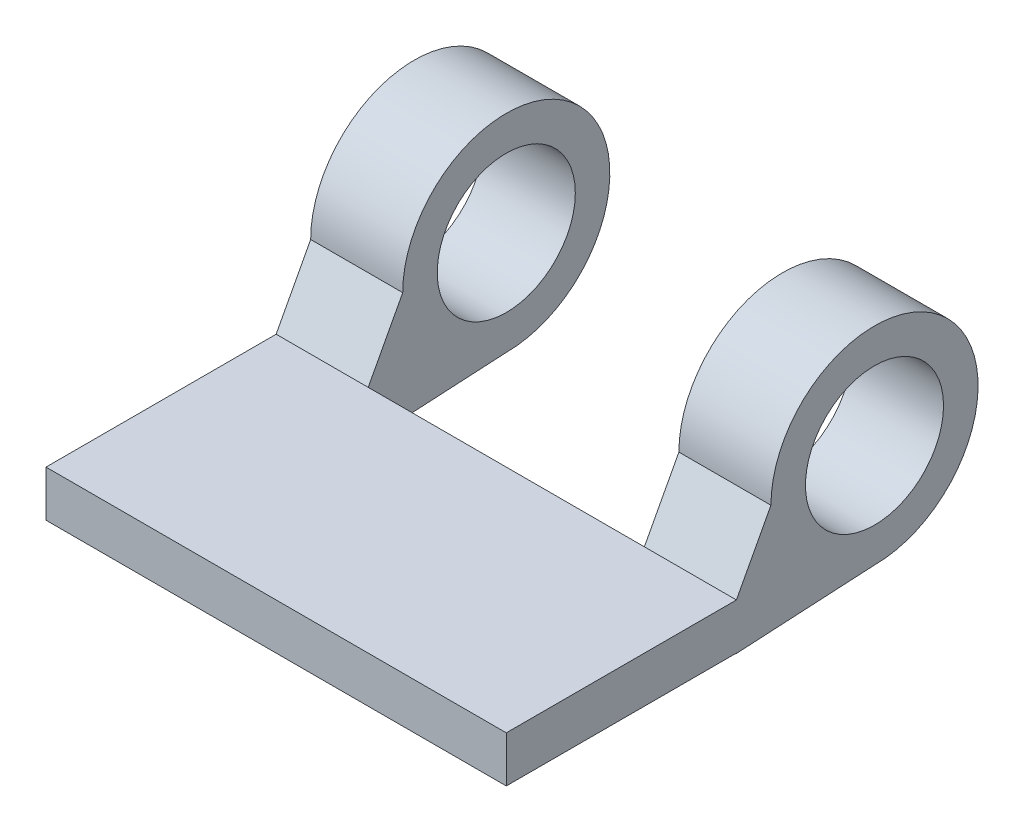
SolidWorks part; units mm, degrees
ref_plane "Front Plane" through (0, 0, 0) normal (0, 0, 1) x (1, 0, 0)
ref_plane "Top Plane" through (0, 0, 0) normal (0, 1, 0) x (1, 0, 0)
ref_plane "Right Plane" through (0, 0, 0) normal (1, 0, 0) x (0, 0, -1)
sketch "Sketch1" plane through (0, 0, 0) normal (0, 1, 0) x (1, 0, 0)
  line L0 (-10, 0) -> (10, 0)
  line L1 (6, 0) -> (6, 4.8205) construction
  line L2 (0, -55) -> (0, 55) construction
  line L3 (-6, 0) -> (-6, 4.8205) construction
  line L5 (-10, 0) -> (10, 0)
  line L6 (-10, 0) -> (-10, -10)
  line L7 (-10, -10) -> (10, -10)
  line L8 (10, 0) -> (10, -10)
  point P4 (0, 0)
  dimension "D1" = 6
  dimension "D2" = 20
extrude "Boss-Extrude1" add sketch "Sketch1" along normal blind 2 contours L8 L0 L6 L7
ref_plane "Plane1" through (6, 0, 0) normal (1, 0, 0) x (0, 0, -1)
sketch "Sketch4" plane through (6, 0, 0) normal (1, 0, 0) x (0, 0, -1)
  line L0 (0, 2) -> (1.5, 4.8144)
  line L2 (0, 2) -> (0, -0.014)
  line L3 (6, 0.3144) -> (0, -0.014)
  circle A0 centre (6, 4.8144) radius 3
  arc A1 (6, 0.3144) -> (1.5, 4.8144) centre (6, 4.8144) ccw
extrude "Boss-Extrude2" add sketch "Sketch4" along normal blind 4
mirror "Mirror1" about plane through (0, 0, 0) normal (1, 0, 0) of "Boss-Extrude2"
